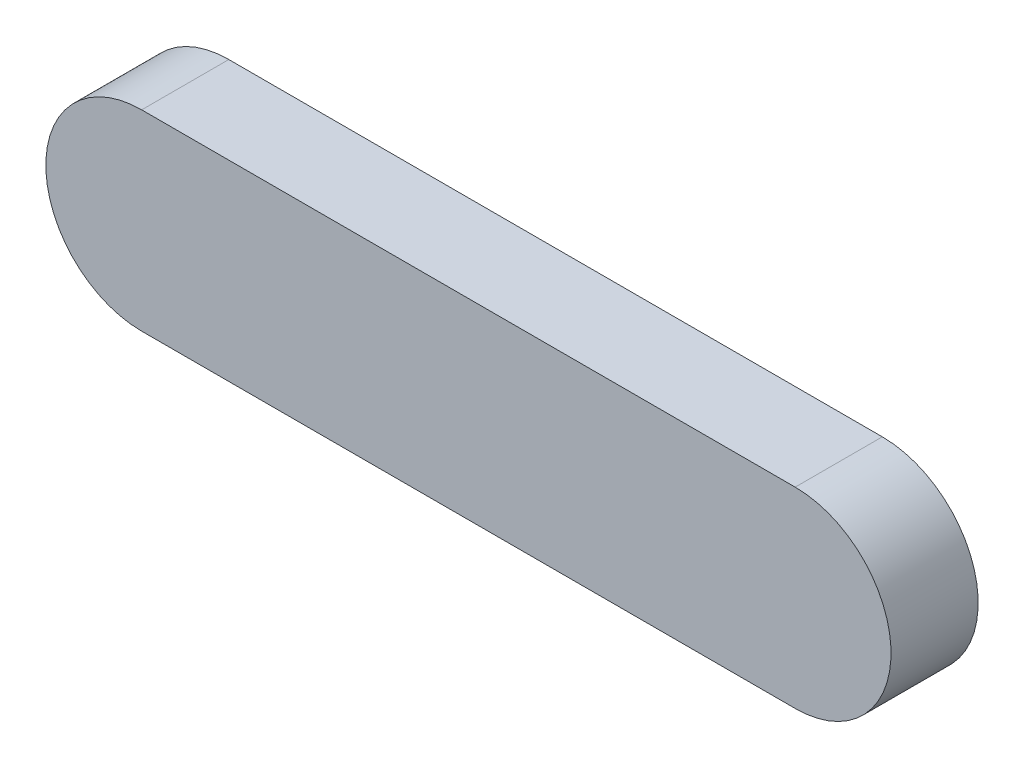
SolidWorks part; units mm, degrees
ref_plane "Front Plane" through (0, 0, 0) normal (0, 0, 1) x (1, 0, 0)
ref_plane "Top Plane" through (0, 0, 0) normal (0, 1, 0) x (1, 0, 0)
ref_plane "Right Plane" through (0, 0, 0) normal (1, 0, 0) x (0, 0, -1)
sketch "草图3" plane through (0, 0, 0) normal (0, 0, 1) x (1, 0, 0)
  line L0 (20, 50) -> (95, 50) construction
  line L1 (20, 61) -> (95, 61)
  line L2 (20, 39) -> (95, 39)
  arc A0 (20, 61) -> (20, 39) centre (20, 50) ccw
  arc A1 (95, 39) -> (95, 61) centre (95, 50) ccw
  point P2 (57.5, 50)
  point P7 (0, 0)
  dimension "width" = 22
  dimension "end1_x" = 20
  dimension "end2_x" = 95
  dimension "end1_y" = 50
extrude "CouplerLink" add sketch "草图3" along normal blind 10
